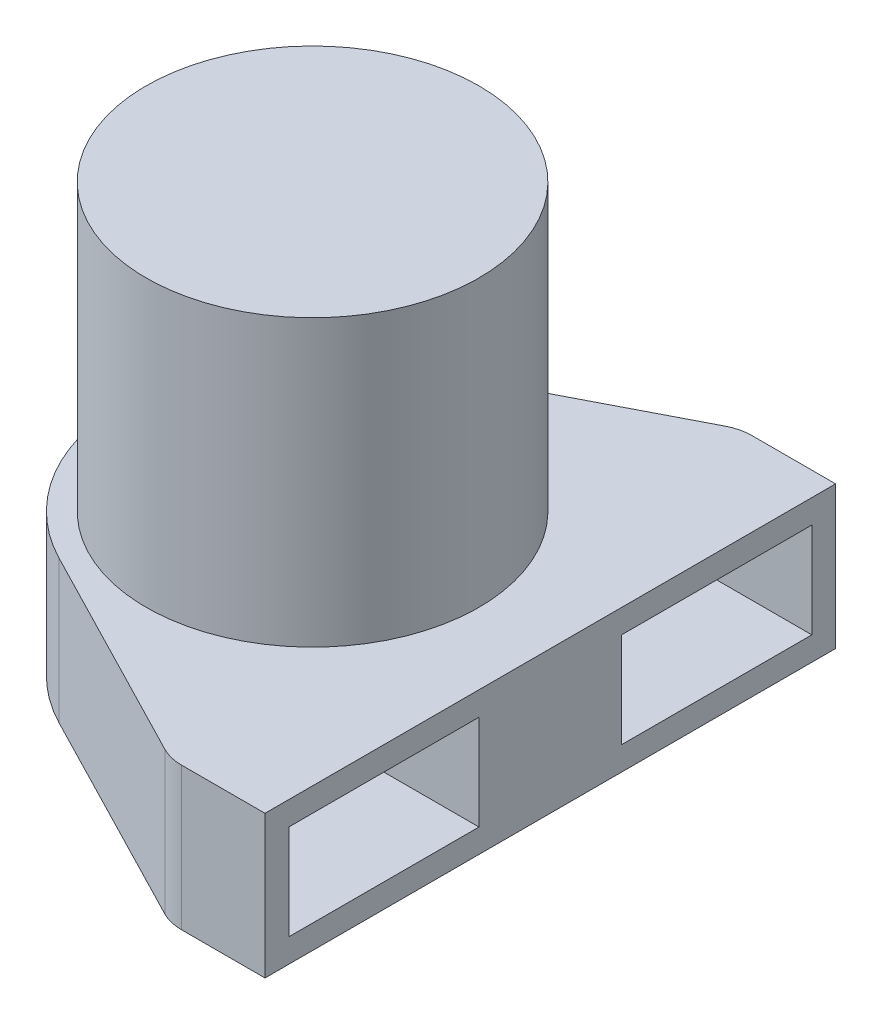
SolidWorks part; units mm, degrees
material "Aleación 1060"
ref_plane "Alzado" through (0, 0, 0) normal (0, 0, 1) x (1, 0, 0)
ref_plane "Planta" through (0, 0, 0) normal (0, 1, 0) x (1, 0, 0)
ref_plane "Vista lateral" through (0, 0, 0) normal (1, 0, 0) x (0, 0, -1)
sketch "Croquis1" plane through (0, 0, 0) normal (0, 1, 0) x (1, 0, 0)
  circle A0 centre (0, 0) radius 35
  dimension "D1" = 70
extrude "Saliente-Extruir1" add sketch "Croquis1" along normal blind 90
sketch "Croquis2" plane through (0, 0, 0) normal (0, -1, 0) x (1, 0, 0)
  line L0 (0, 0) -> (50, 0) construction
  line L1 (50, 60) -> (50, -60)
  line L2 (50, -60) -> (32.4261, -60)
  line L3 (27.8436, -58.8883) -> (-18.1383, -35.1819)
  line L4 (50, 60) -> (32.4261, 60)
  line L5 (27.8436, 58.8883) -> (-18.1383, 35.1819)
  arc A0 (-18.1383, 35.1819) -> (-18.1383, -35.1819) centre (0, 0) ccw
  arc A1 (32.4261, -60) -> (27.8436, -58.8883) centre (32.4261, -50) cw
  arc A2 (32.4261, 60) -> (27.8436, 58.8883) centre (32.4261, 50) ccw
  point P9 (30, -60)
  point P11 (30, 60)
  dimension "D4" = 10
  dimension "D1" = 50
  dimension "D2" = 60
  dimension "D3" = 20
extrude "Saliente-Extruir2" add sketch "Croquis2" against normal blind 30
sketch "Croquis3" plane through (50, 0, 0) normal (1, 0, 0) x (0, 0, -1)
  line L0 (0, 0) -> (0, 30) construction
  line L1 (60, 0) -> (-60, 0) construction
  line L2 (60, 30) -> (-60, 30) construction
  line L3 (-60, 30) -> (-60, 0) construction
  line L4 (-15, 5) -> (-55, 5)
  line L5 (-15, 5) -> (-15, 25)
  line L6 (-15, 25) -> (-55, 25)
  line L7 (-55, 5) -> (-55, 25)
  line L8 (-15, 5) -> (-55, 25) construction
  line L9 (-15, 25) -> (-55, 5) construction
  line L10 (55, 5) -> (55, 25)
  line L11 (15, 5) -> (15, 25)
  line L12 (15, 5) -> (55, 5)
  line L13 (15, 25) -> (55, 25)
  point P6 (-35, 15)
  dimension "D1" = 25
  dimension "D2" = 20
  dimension "D3" = 40
extrude "Cortar-Extruir1" cut sketch "Croquis3" against normal blind 28
